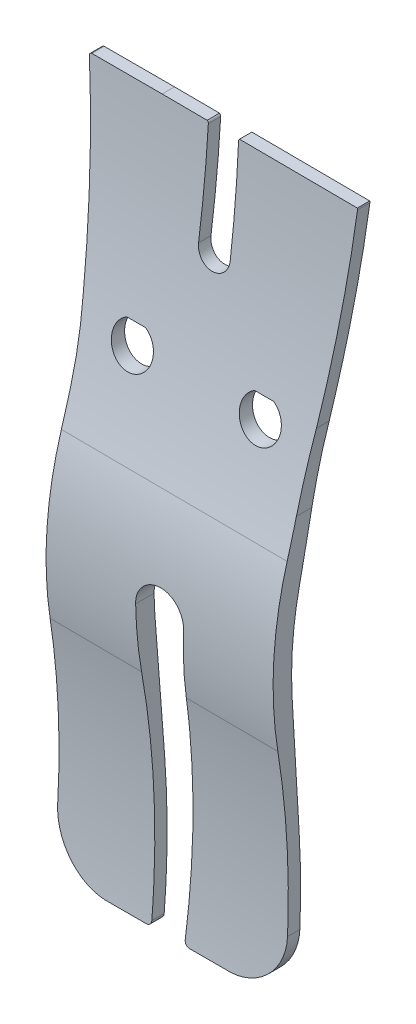
SolidWorks part; units mm, degrees
material "Thornel Mat VMA"
ref_plane "Front Plane" through (0, 0, 0) normal (0, 0, 1) x (1, 0, 0)
ref_plane "Top Plane" through (0, 0, 0) normal (0, 1, 0) x (1, 0, 0)
ref_plane "Right Plane" through (0, 0, 0) normal (1, 0, 0) x (0, 0, -1)
sketch "Sketch2" plane through (0, 0, 0) normal (0, 0, 1) x (1, 0, 0)
  line L0 (733.881, 512.4095) -> (733.7146, 485.3986)
  line L1 (744.9772, 473.3952) -> (754.1807, 473.3952)
  line L2 (755.2308, 474.4733) -> (753.6442, 534.7768)
  line L3 (764.1405, 534.7768) -> (762.5539, 474.4733)
  line L4 (763.604, 473.3952) -> (772.8075, 473.3952)
  line L5 (784.0701, 485.3986) -> (783.9037, 512.4095)
  line L6 (753.8376, 620.4126) -> (730.0432, 620.4126)
  line L7 (729.5203, 619.8381) -> (733.3641, 579.043)
  line L8 (753.8376, 620.4126) -> (755.0481, 620.4126)
  line L9 (783.9037, 512.4095) -> (783.5878, 563.7039)
  line L10 (784.4206, 579.043) -> (788.2644, 619.8381)
  line L11 (787.7415, 620.4126) -> (763.947, 620.4302)
  line L12 (763.947, 620.4302) -> (762.7206, 620.4302)
  line L13 (762.1958, 619.8843) -> (762.351, 598.1739)
  line L14 (755.573, 619.8667) -> (755.4177, 598.1739)
  line L15 (734.1969, 563.7039) -> (733.881, 512.4095)
  arc A0 (733.7146, 485.3986) -> (744.9772, 473.3952) centre (745.7379, 485.3944) ccw
  arc A1 (754.1807, 473.3952) -> (755.2308, 474.4733) centre (754.1807, 474.4457) ccw
  arc A2 (758.8923, 540.3055) -> (753.6442, 534.7768) centre (758.8895, 535.053) ccw
  arc A3 (764.1405, 534.7768) -> (758.8923, 540.3055) centre (758.8952, 535.053) ccw
  arc A4 (762.5539, 474.4733) -> (763.604, 473.3952) centre (763.604, 474.4457) ccw
  arc A5 (772.8075, 473.3952) -> (784.0701, 485.3986) centre (772.0508, 485.3907) ccw
  arc A6 (755.573, 619.8667) -> (755.0481, 620.4126) centre (755.0481, 619.8874) ccw
  arc A7 (730.0432, 620.4126) -> (729.5203, 619.8381) centre (730.0432, 619.8874) ccw
  arc A8 (733.5935, 576.8903) -> (733.3641, 579.043) centre (606.9537, 564.4877) ccw
  arc A9 (762.7206, 620.4302) -> (762.1958, 619.8843) centre (762.7206, 619.905) ccw
  arc A10 (784.4206, 579.043) -> (783.5878, 563.7039) centre (910.831, 564.4877) ccw
  arc A11 (788.2644, 619.8381) -> (787.7415, 620.4126) centre (787.7415, 619.8874) ccw
  arc A12 (755.4177, 598.1739) -> (762.351, 598.1739) centre (758.8844, 598.1739) ccw
  arc A13 (734.1969, 563.7039) -> (733.5935, 576.8903) centre (606.9537, 564.4877) ccw
extrude "Boss-Extrude1" add sketch "Sketch2" along normal blind 92
sketch "Sketch3" plane through (730.6969, -4.501, 0) normal (-1, 0.0062, 0) x (0, 0, 1)
  line L0 (43.1436, 477.975) -> (40.4245, 477.975)
  line L1 (39.433, 508.3613) -> (40.8121, 534.581)
  line L2 (30.9385, 624.9925) -> (28.2351, 624.9925)
  arc A0 (30.9385, 624.9925) -> (41.7507, 561.026) centre (308.2863, 638.975) ccw
  arc A1 (44.0042, 526.1968) -> (41.7507, 561.026) centre (-35.0331, 538.5703) ccw
  arc A2 (44.0042, 526.1968) -> (43.1436, 477.975) centre (217.8863, 498.975) ccw
  arc A3 (39.433, 508.3613) -> (40.4245, 477.975) centre (217.8863, 498.975) ccw
  arc A4 (40.8121, 534.581) -> (39.1927, 554.6617) centre (-35.0331, 538.5703) ccw
  arc A5 (32.3265, 589.2721) -> (39.1927, 554.6617) centre (1016.4911, 766.5292) ccw
  arc A6 (28.2351, 624.9925) -> (32.3265, 589.2721) centre (308.2863, 638.975) ccw
extrude "Cut-Extrude1" cut sketch "Sketch3" against normal blind 118 and the other way blind 79 flip side to cut
sketch "Sketch4" plane through (0, 0, 0) normal (0, 0, 1) x (1, 0, 0)
  line L0 (749.5789, 473.3952) -> (768.2057, 473.3952) construction
  line L1 (744.9772, 473.3952) -> (754.1807, 473.3952) construction
  line L2 (763.604, 473.3952) -> (772.8075, 473.3952) construction
  line L3 (758.8923, 473.3952) -> (758.8923, 623.2544) construction
  line L4 (770.8308, 579.3952) -> (772.8923, 579.3952) construction
  line L5 (744.8923, 579.3952) -> (746.9539, 579.3952) construction
  line L7 (770.8308, 579.3952) -> (774.9539, 579.3952)
  line L8 (742.8308, 579.3952) -> (746.9539, 579.3952)
  arc A0 (770.8308, 579.3952) -> (774.9539, 579.3952) centre (772.8923, 575.3952) ccw
  arc A1 (742.8308, 579.3952) -> (746.9539, 579.3952) centre (744.8923, 575.3952) ccw
  dimension "D3" = 9
  dimension "D4" = 9
  dimension "D1" = 14
  dimension "D2" = 14
  dimension "D6" = 102
  dimension "D7" = 4.1231
extrude "Cut-Extrude2" cut sketch "Sketch4" along normal blind 81
